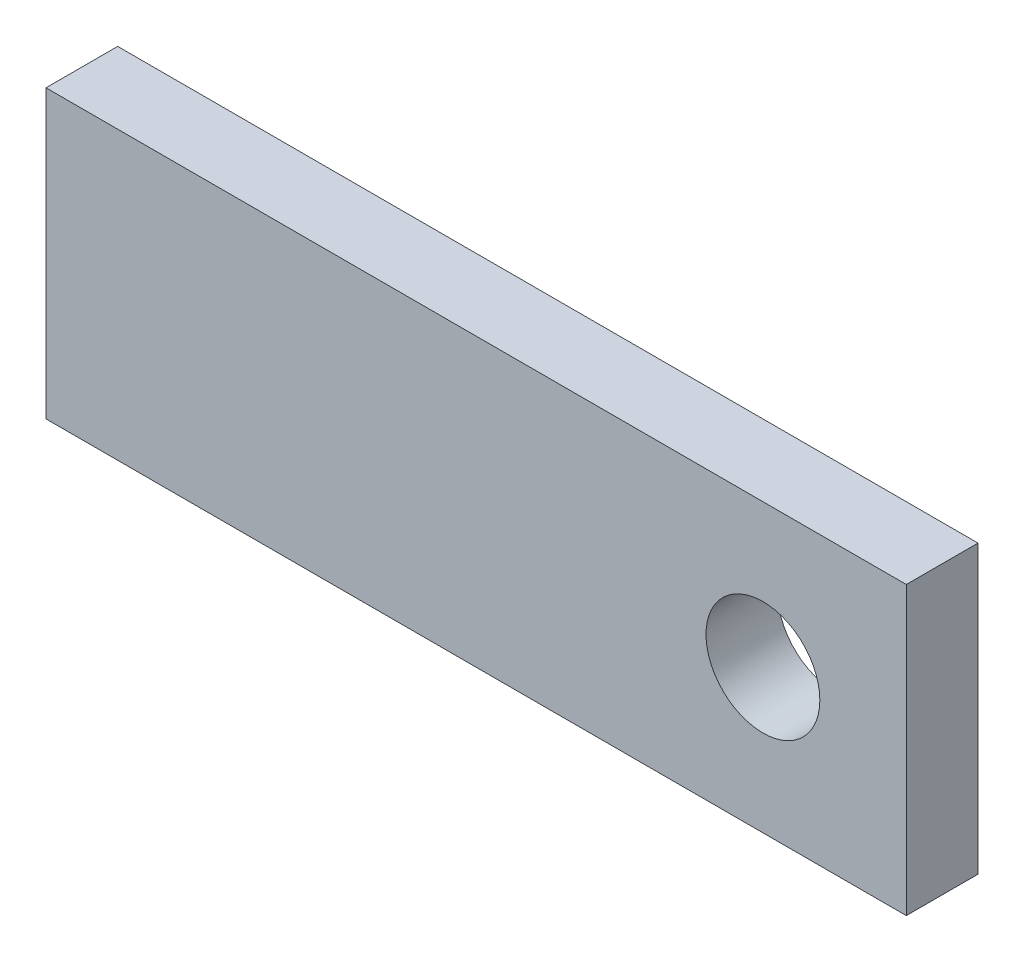
SolidWorks part; units mm, degrees
material "Plain Carbon Steel"
ref_plane "Front Plane" through (0, 0, 0) normal (0, 0, 1) x (1, 0, 0)
ref_plane "Top Plane" through (0, 0, 0) normal (0, 1, 0) x (1, 0, 0)
ref_plane "Right Plane" through (0, 0, 0) normal (1, 0, 0) x (0, 0, -1)
sketch "Sketch1" plane through (0, 0, 0) normal (0, 0, 1) x (1, 0, 0)
  line L1 (-38.1, -12.7) -> (38.1, -12.7)
  line L2 (-38.1, -12.7) -> (-38.1, 12.7)
  line L3 (-38.1, 12.7) -> (38.1, 12.7)
  line L4 (38.1, -12.7) -> (38.1, 12.7)
  line L5 (-38.1, -12.7) -> (38.1, 12.7) construction
  line L6 (-38.1, 12.7) -> (38.1, -12.7) construction
  point P0 (0, 0)
  dimension "D1" = 76.2
  dimension "D2" = 25.4
extrude "Extrude1" add sketch "Sketch1" along normal blind 6.35
sketch "Sketch2" plane through (0, 0, 6.35) normal (0, 0, 1) x (1, 0, 0)
  line L0 (38.1, 0) -> (25.4, 0) construction
  line L1 (38.1, -12.7) -> (38.1, 12.7) construction
  dimension "D1" = 12.7
hole_wizard "3/8 Clearance Hole1" positions "3DSketch1" profile "Sketch3" hole size "3/8" standard "Ansi Inch"
sketch3d "3DSketch1"
  point P0 (25.4, 0, 6.35)
sketch "Sketch3" plane through (25.4, 0, 6.35) normal (1, 0, 0) x (0, -1, 0)
  line L0 (0, 0) -> (0, 19.0315)
  line L1 (0, 19.0315) -> (5.0419, 16.002)
  line L2 (5.0419, 16.002) -> (5.0419, 0)
  line L5 (5.0419, 0) -> (0, 0)
  line L10 (0, 19.0315) -> (-5.0419, 16.002) construction
  line L11 (0, -6.35) -> (0, 107.95) construction
  dimension "Hole Dia." = 10.0838
  dimension "Hole Depth" = 16.002
  dimension "Drill Angle" = 118
